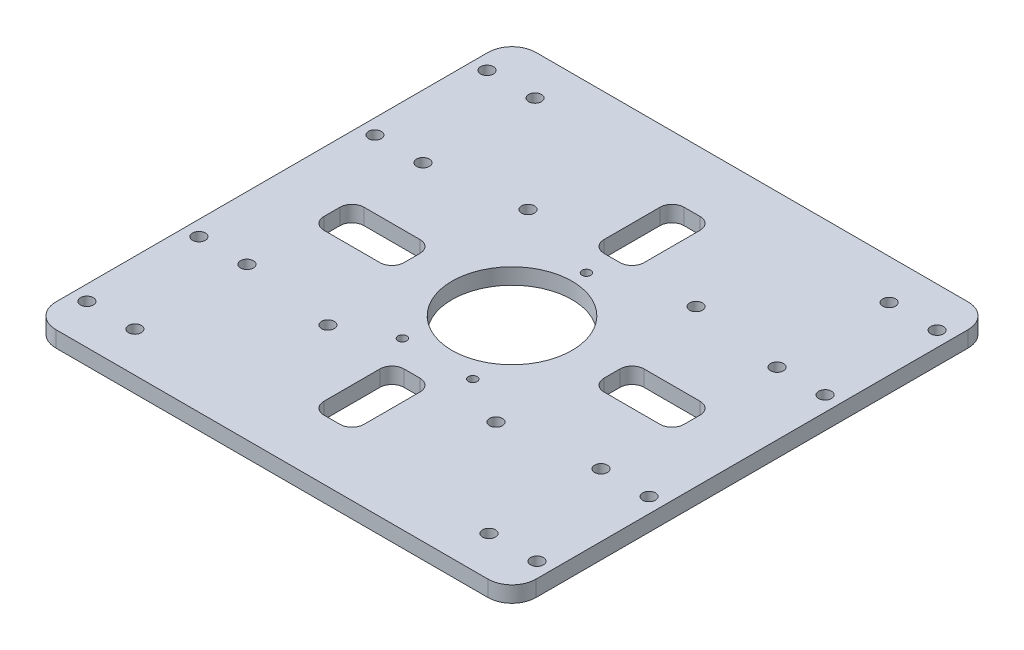
SolidWorks part; units mm, degrees
material "自定义塑料"
ref_plane "前视基准面" through (0, 0, 0) normal (0, 0, 1) x (1, 0, 0)
ref_plane "上视基准面" through (0, 0, 0) normal (0, 1, 0) x (1, 0, 0)
ref_plane "右视基准面" through (0, 0, 0) normal (1, 0, 0) x (0, 0, -1)
sketch "草图1" plane through (0, 0, 0) normal (0, 1, 0) x (1, 0, 0)
  line L0 (0, 0) -> (-20.2314, 0) construction
  line L1 (-54, 60) -> (54, 60)
  line L2 (-60, 54) -> (-60, -54)
  line L3 (-54, -60) -> (54, -60)
  line L4 (60, 54) -> (60, -54)
  line L5 (-60, 60) -> (60, -60) construction
  line L6 (-60, -60) -> (60, 60) construction
  line L7 (0, 0) -> (0, 21.0425) construction
  line L8 (-56.25, 60) -> (-56.25, 50) construction
  line L9 (-44.25, 36) -> (-56.25, 36) construction
  line L10 (-56.25, 50) -> (-44.25, 50) construction
  line L11 (-56.25, 50) -> (-56.25, 22) construction
  line L12 (-56.25, 22) -> (-44.25, 22) construction
  line L13 (-44.25, 50) -> (-44.25, 22) construction
  line L15 (50.25, -36) -> (-50.25, -36) construction
  line L16 (50.25, -36) -> (50.25, 36) construction
  line L17 (50.25, 36) -> (-50.25, 36) construction
  line L18 (-50.25, -36) -> (-50.25, 36) construction
  line L19 (50.25, -36) -> (-50.25, 36) construction
  line L20 (50.25, 36) -> (-50.25, -36) construction
  line L21 (-2, -25) -> (2, -25)
  line L22 (-5, -28) -> (-5, -42)
  line L23 (-2, -45) -> (2, -45)
  line L24 (5, -28) -> (5, -42)
  line L25 (-5, -25) -> (5, -45) construction
  line L26 (-5, -45) -> (5, -25) construction
  line L38 (0, 0) -> (0, -52.4488) construction
  line L51 (-45, 2) -> (-45, -2)
  line L52 (-28, -5) -> (-42, -5)
  line L53 (-25, 2) -> (-25, -2)
  line L54 (-28, 5) -> (-42, 5)
  line L55 (2, 45) -> (-2, 45)
  line L56 (-5, 28) -> (-5, 42)
  line L57 (2, 25) -> (-2, 25)
  line L58 (5, 28) -> (5, 42)
  line L59 (45, -2) -> (45, 2)
  line L60 (28, 5) -> (42, 5)
  line L61 (25, -2) -> (25, 2)
  line L62 (28, -5) -> (42, -5)
  circle A16 centre (0, 18.6) radius 1.1
  circle A17 centre (8.8, -18.6) radius 1.1
  circle A18 centre (-8.8, -18.6) radius 1.1
  circle A19 centre (-21, 25) radius 1.6
  circle A20 centre (21, 25) radius 1.6
  circle A21 centre (21, -25) radius 1.6
  circle A22 centre (-21, -25) radius 1.6
  arc A23 (-60, -54) -> (-54, -60) centre (-54, -54) ccw
  arc A24 (54, -60) -> (60, -54) centre (54, -54) ccw
  arc A25 (-54, 60) -> (-60, 54) centre (-54, 54) ccw
  arc A26 (54, 60) -> (60, 54) centre (54, 54) cw
  circle A27 centre (-56.25, 50) radius 1.6
  circle A28 centre (-44.25, 50) radius 1.6
  circle A29 centre (-44.25, 22) radius 1.6
  circle A30 centre (-56.25, 22) radius 1.6
  circle A31 centre (56.25, 22) radius 1.6
  circle A32 centre (44.25, 22) radius 1.6
  circle A33 centre (44.25, 50) radius 1.6
  circle A34 centre (56.25, 50) radius 1.6
  circle A35 centre (56.25, -50) radius 1.6
  circle A36 centre (44.25, -50) radius 1.6
  circle A37 centre (44.25, -22) radius 1.6
  circle A38 centre (56.25, -22) radius 1.6
  circle A39 centre (-44.25, -50) radius 1.6
  circle A40 centre (-56.25, -50) radius 1.6
  circle A41 centre (-56.25, -22) radius 1.6
  circle A42 centre (-44.25, -22) radius 1.6
  circle A43 centre (0, 0) radius 15
  arc A56 (-2, -25) -> (-5, -28) centre (-2, -28) ccw
  arc A57 (2, -25) -> (5, -28) centre (2, -28) cw
  arc A58 (-5, -42) -> (-2, -45) centre (-2, -42) ccw
  arc A59 (2, -45) -> (5, -42) centre (2, -42) ccw
  arc A69 (-45, -2) -> (-42, -5) centre (-42, -2) ccw
  arc A71 (-25, -2) -> (-28, -5) centre (-28, -2) cw
  arc A72 (-25, 2) -> (-28, 5) centre (-28, 2) ccw
  arc A74 (-42, 5) -> (-45, 2) centre (-42, 2) ccw
  arc A75 (-2, 45) -> (-5, 42) centre (-2, 42) ccw
  arc A77 (-2, 25) -> (-5, 28) centre (-2, 28) cw
  arc A78 (2, 25) -> (5, 28) centre (2, 28) ccw
  arc A79 (5, 42) -> (2, 45) centre (2, 42) ccw
  arc A80 (45, 2) -> (42, 5) centre (42, 2) ccw
  arc A81 (25, 2) -> (28, 5) centre (28, 2) cw
  arc A82 (25, -2) -> (28, -5) centre (28, -2) ccw
  arc A83 (42, -5) -> (45, -2) centre (42, -2) ccw
  point P0 (0, 0)
  point P28 (0, -35)
  dimension "D4" = 3.75
  dimension "D9" = 2.2
  dimension "D15" = 3.2
  dimension "D16" = 6
  dimension "D17" = 3.2
  dimension "D20" = 30
  dimension "D24" = 25
  dimension "D1" = 120
  dimension "D2" = 120
  dimension "D3" = 10
  dimension "D5" = 28
  dimension "D6" = 12
  dimension "D7" = 2
  dimension "D8" = 2
  dimension "D10" = 18.6
  dimension "D11" = 18.6
  dimension "D12" = 8.8
  dimension "D13" = 42
  dimension "D14" = 50
  dimension "D21" = 10
  dimension "D22" = 20
  dimension "D18" = 2
  dimension "D19" = 2
  dimension "D23" = 4
extrude "凸台-拉伸1" add sketch "草图1" along normal blind 4
